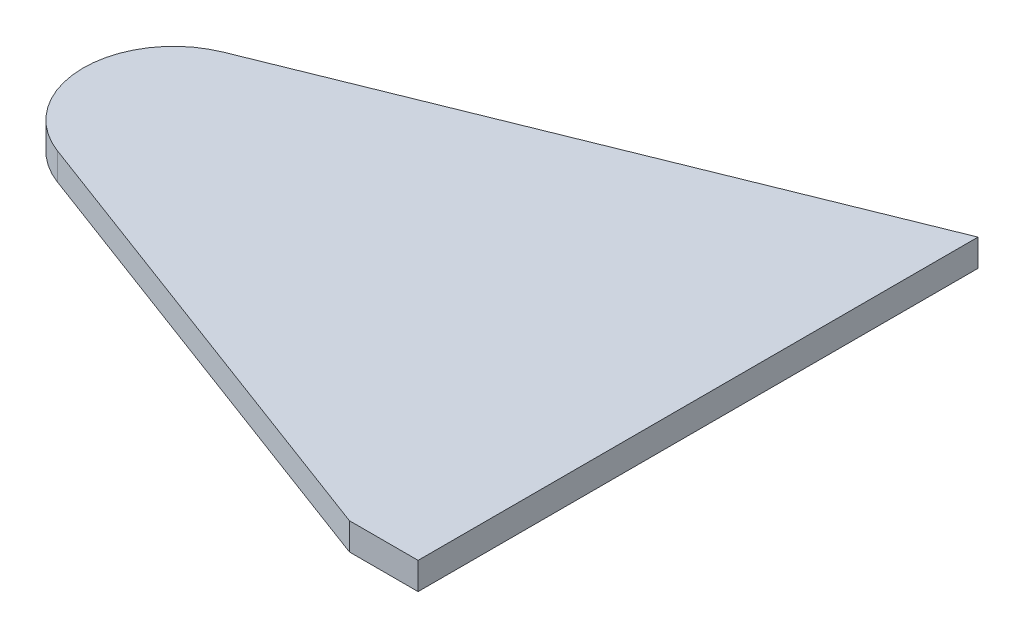
SolidWorks part; units mm, degrees
ref_plane "Front Plane" through (0, 0, 0) normal (0, 0, 1) x (1, 0, 0)
ref_plane "Top Plane" through (0, 0, 0) normal (0, 1, 0) x (1, 0, 0)
ref_plane "Right Plane" through (0, 0, 0) normal (1, 0, 0) x (0, 0, -1)
sketch "Sketch1" plane through (0, 0, 0) normal (0, 1, 0) x (1, 0, 0)
  line L0 (0, 0) -> (38, 0)
  line L1 (0, 0) -> (-262.2682, 98.0581)
  line L2 (-258.6988, 190.1259) -> (-378.767, 141.6152)
  line L3 (38, 0) -> (38, 310)
  line L4 (-258.6988, 190.1259) -> (38, 310)
  line L5 (-262.2682, 98.0581) -> (-378.767, 141.6152)
  line L6 (-378.767, 141.6152) -> (-274.977, 141.6152) construction
  dimension "D1" = 38
  dimension "D2" = 159.5
  dimension "D3" = 280
  dimension "D4" = 320
  dimension "D5" = 22
  dimension "D6" = 310
extrude "Boss-Extrude1" add sketch "Sketch1" along normal blind 15
fillet "Fillet1" radius 50 1 edges at (-378.767, 7.5, -141.6152)
